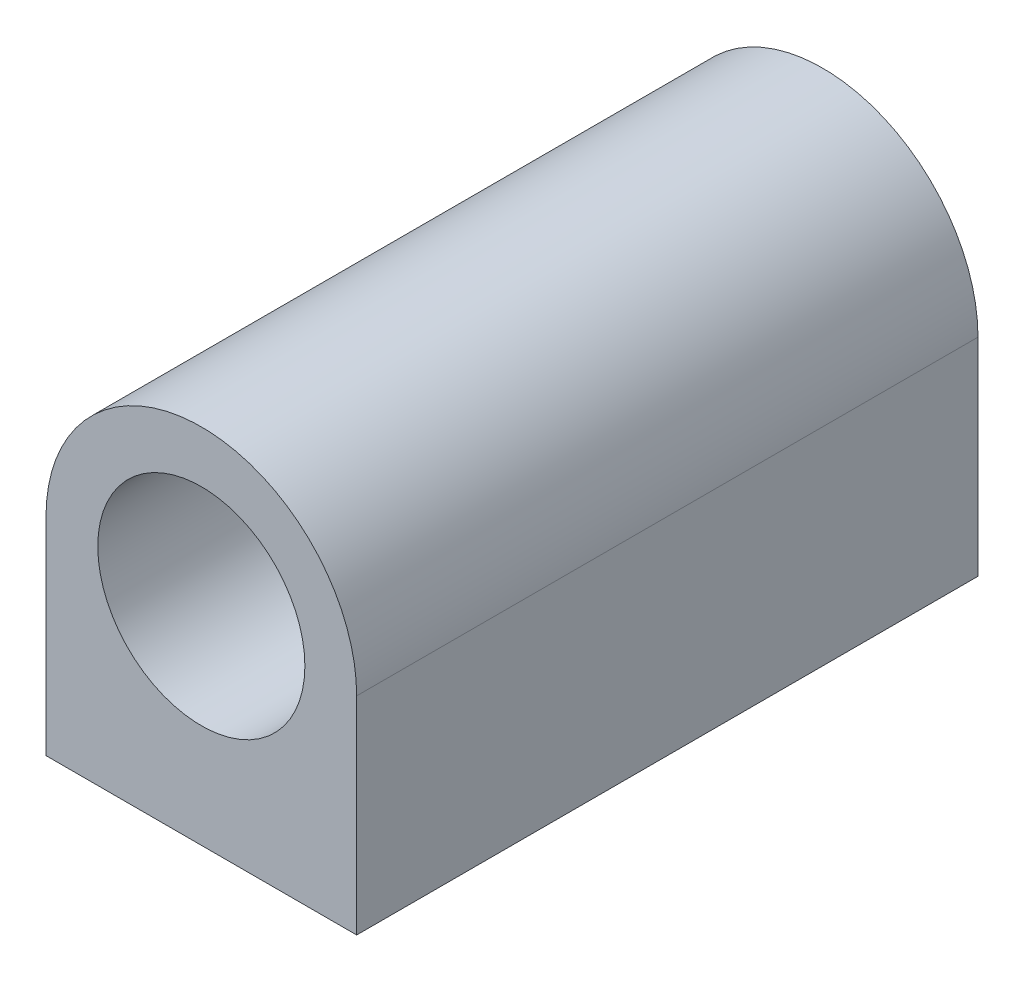
SolidWorks part; units mm, degrees
ref_plane "Front Plane" through (0, 0, 0) normal (0, 0, 1) x (1, 0, 0)
ref_plane "Top Plane" through (0, 0, 0) normal (0, 1, 0) x (1, 0, 0)
ref_plane "Right Plane" through (0, 0, 0) normal (1, 0, 0) x (0, 0, -1)
sketch "Sketch1" plane through (0, 0, 0) normal (0, 0, 1) x (1, 0, 0)
  line L0 (-19.05, 25.4) -> (-19.05, 0)
  line L1 (-19.05, 0) -> (19.05, 0)
  line L2 (19.05, 0) -> (19.05, 25.4)
  arc A0 (19.05, 25.4) -> (-19.05, 25.4) centre (0, 25.4) ccw
  circle A1 centre (0, 25.4) radius 12.7
  dimension "D1" = 38.1
  dimension "D3" = 25.4
  dimension "D2" = 25.4
extrude "Boss-Extrude1" add sketch "Sketch1" along normal mid plane 76.2
hole_wizard "Hole1" positions "Sketch2" profile "Sketch3" legacy
sketch "Sketch2" plane through (0, 0, 0) normal (0, -1, 0) x (-1, 0, 0)
  line L0 (19.05, 38.1) -> (-19.05, 38.1) construction
  point P0 (-12.7, 31.75)
  dimension "D1" = 6.35
  dimension "D2" = 12.7
sketch "Sketch3" plane through (12.7, 0, -31.75) normal (1, 0, 0) x (0, 0, -1)
  line L0 (0, 0) -> (0, 12.7)
  line L1 (0, 12.7) -> (1.651, 12.7)
  line L2 (1.651, 12.7) -> (1.651, 0)
  line L3 (1.651, 0) -> (0, 0)
  line L4 (0, 110) -> (0, -10) construction
  dimension "Diameter" = 3.302
  dimension "Depth" = 12.7
pattern_linear "LPattern1" count 2 spacing 63.5 along (0, 0, 1) count 2 spacing 25.4 along (-1, 0, 0) of "Hole1"
